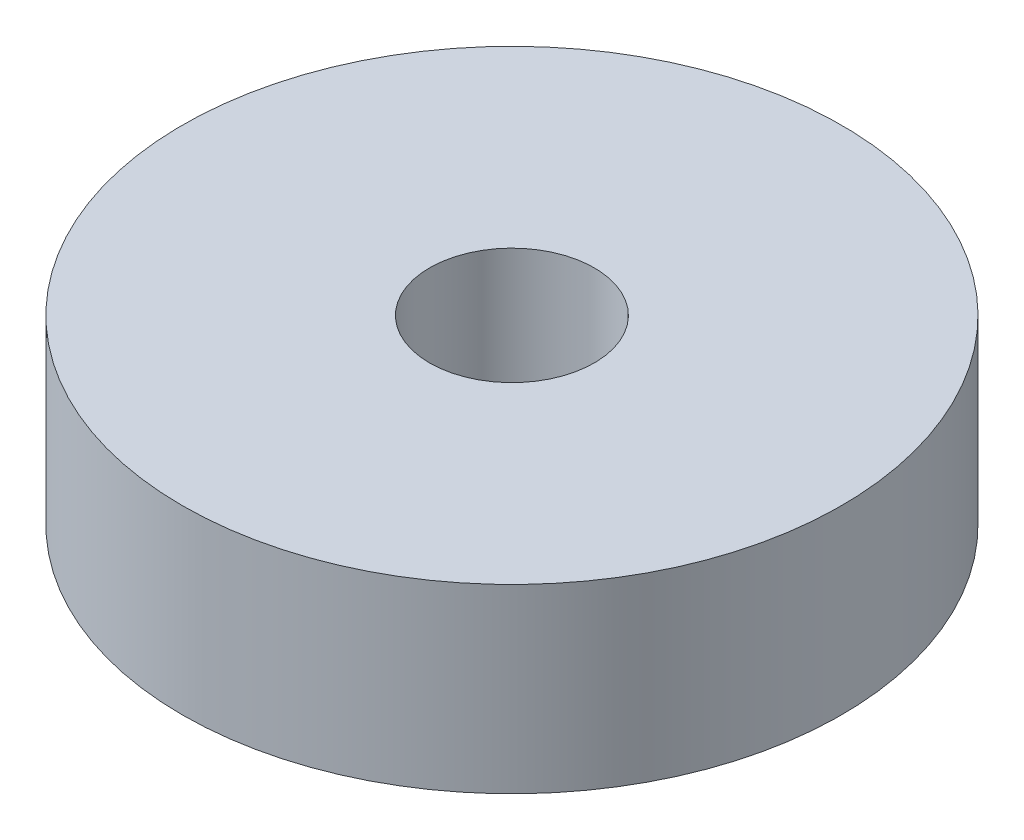
SolidWorks part; units mm, degrees
ref_plane "Front Plane" through (0, 0, 0) normal (0, 0, 1) x (1, 0, 0)
ref_plane "Top Plane" through (0, 0, 0) normal (0, 1, 0) x (1, 0, 0)
ref_plane "Right Plane" through (0, 0, 0) normal (1, 0, 0) x (0, 0, -1)
sketch "Sketch1" plane through (0, 0, 0) normal (0, 1, 0) x (1, 0, 0)
  circle A0 centre (0, 0) radius 25.4
  circle A1 centre (0, 0) radius 6.35
  dimension "D1" = 50.8
  dimension "D2" = 12.7
extrude "Boss-Extrude1" add sketch "Sketch1" along normal blind 13.97
fillet "Fillet1" [suppressed] radius 2.54
